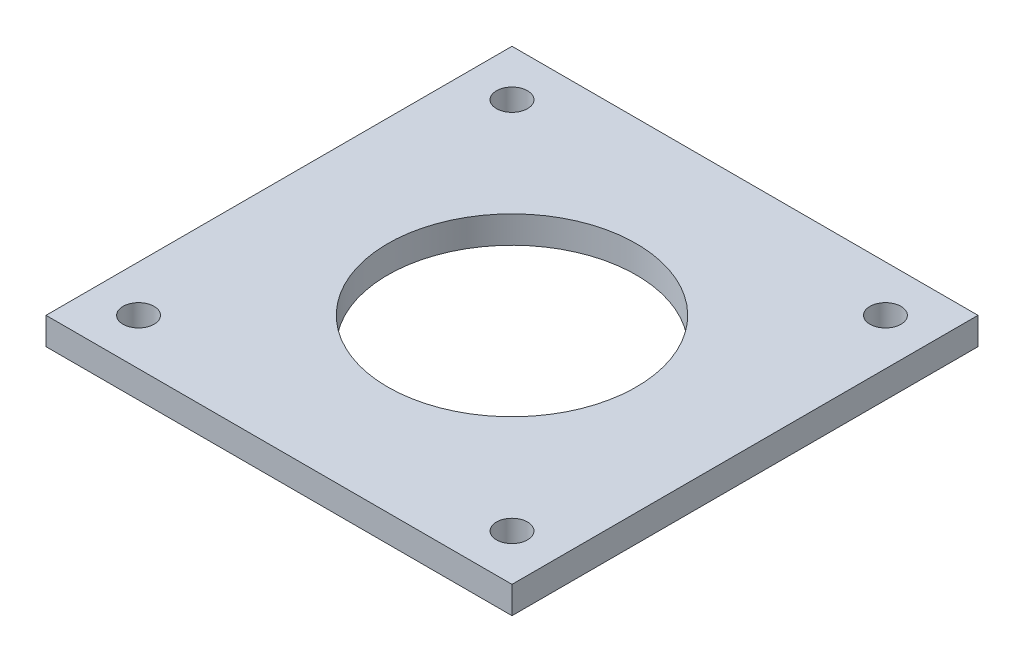
SolidWorks part; units mm, degrees
ref_plane "Front" through (0, 0, 0) normal (0, 0, 1) x (1, 0, 0)
ref_plane "Top" through (0, 0, 0) normal (0, 1, 0) x (1, 0, 0)
ref_plane "Right" through (0, 0, 0) normal (1, 0, 0) x (0, 0, -1)
sketch "Sketch1" plane through (0, 0, 0) normal (0, 1, 0) x (1, 0, 0)
  line L1 (-30, -30) -> (30, -30)
  line L2 (-30, -30) -> (-30, 30)
  line L3 (-30, 30) -> (30, 30)
  line L4 (30, -30) -> (30, 30)
  line L5 (-30, -30) -> (30, 30) construction
  line L6 (-30, 30) -> (30, -30) construction
  circle A0 centre (0, 0) radius 16
  circle A1 centre (24.0416, -24.0416) radius 2
  circle A2 centre (24.0416, 24.0416) radius 2
  circle A3 centre (-24.0416, 24.0416) radius 2
  circle A4 centre (-24.0416, -24.0416) radius 2
  point P15 (0, 0)
  point P20 (-11.3137, -11.3137)
  dimension "D1" = 32
  dimension "D3" = 4
  dimension "D2" = 60
  dimension "D4" = 18
extrude "Boss-Extrude1" add sketch "Sketch1" along normal blind 3.5 contours L1 L4 L3 L2 A0
